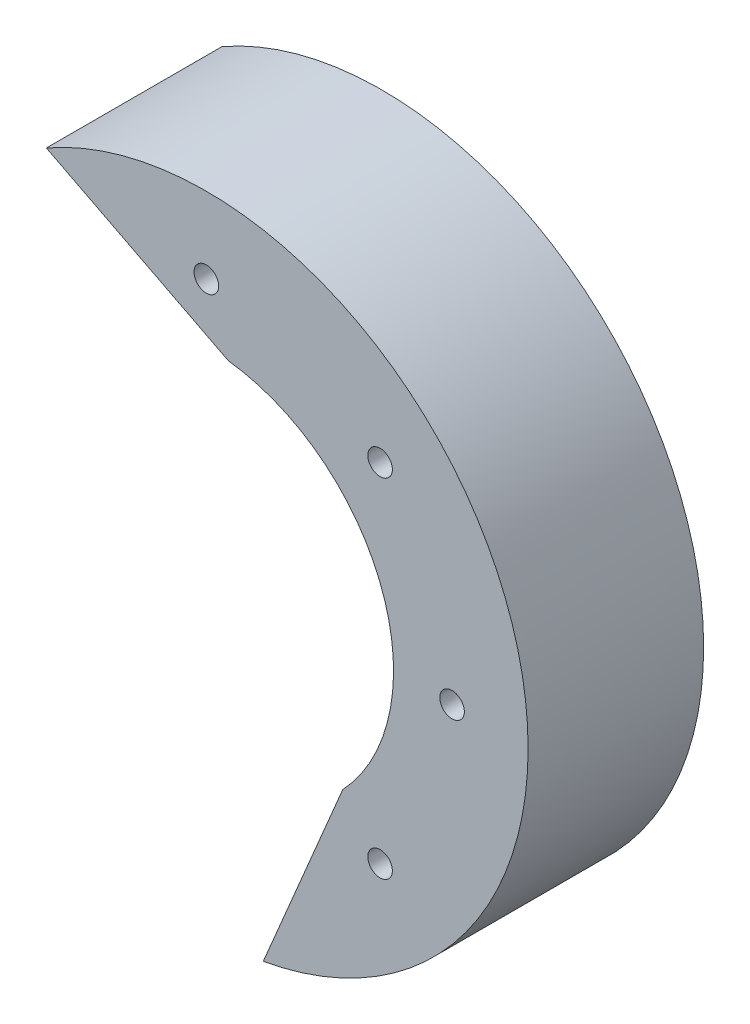
SolidWorks part; units mm, degrees
material "尼龙 101"
ref_plane "前视基准面" through (0, 0, 0) normal (0, 0, 1) x (1, 0, 0)
ref_plane "上视基准面" through (0, 0, 0) normal (0, 1, 0) x (1, 0, 0)
ref_plane "右视基准面" through (0, 0, 0) normal (1, 0, 0) x (0, 0, -1)
sketch "草图1" plane through (0, 0, 0) normal (0, 0, 1) x (1, 0, 0)
  line L0 (0, 55) -> (0, -55) construction
  line L1 (-55, 0) -> (55, 0) construction
  line L2 (0, 0) -> (-138.5641, 80) construction
  line L3 (0, 0) -> (-54.7232, -150.3508) construction
  line L4 (-27.3421, 47.7222) -> (3.7722, 31.7769)
  line L7 (9.73, -54.1325) -> (23.3155, -21.9178)
  arc A0 (9.73, -54.1325) -> (-27.3421, 47.7222) centre (0, 0) ccw
  arc A1 (23.3155, -21.9178) -> (3.7722, 31.7769) centre (0, 0) ccw
  circle A3 centre (-138.5641, 80) radius 22 construction
  circle A4 centre (0, 0) radius 30 construction
  circle A6 centre (-54.7232, -150.3508) radius 22 construction
  dimension "D1" = 110
  dimension "D2" = 64
  dimension "D4" = 160
  dimension "D5" = 44
  dimension "D6" = 60
  dimension "D8" = 20
  dimension "D9" = 44
  dimension "D3" = 150
  dimension "D7" = 160
extrude "凸台-拉伸1" add sketch "草图1" along normal blind 30
sketch "草图2" plane through (0, 0, 30) normal (0, 0, 1) x (1, 0, 0)
  circle A0 centre (0, 0) radius 42 construction
  point P3 (0, 42)
  point P6 (29.6985, 29.6985)
  point P7 (42, 0)
  point P8 (29.6985, -29.6985)
  point P9 (0, -42)
  point P10 (-29.6985, -29.6985)
  point P11 (-42, 0)
  point P12 (-29.6985, 29.6985)
  dimension "D1" = 84
  dimension "D2" = 8
hole_wizard "Ø4.2 (4.2) 直径孔1" positions "3D草图2" profile "草图6" hole size "Ø4.2" standard "GB" end condition through all
sketch3d "3D草图2"
  point P0 (0, 42, 30)
  point P3 (29.6985, 29.6985, 30)
  point P6 (42, 0, 30)
  point P9 (29.6985, -29.6985, 30)
sketch "草图6" plane through (0, 42, 30) normal (1, 0, 0) x (0, -1, 0)
  line L0 (0, 0) -> (0, 30)
  line L1 (0, 30) -> (2.1, 30)
  line L2 (2.1, 30) -> (2.1, 0)
  line L5 (2.1, 0) -> (0, 0)
  line L11 (0, -6.35) -> (0, 107.95) construction
  dimension "通孔孔直径" = 4.2
  dimension "通孔孔深度" = 30
sketch "草图7" plane through (0, 0, 0) normal (0, 0, -1) x (-1, 0, 0)
  circle A0 centre (0, 42) radius 5
  circle A1 centre (-29.6985, 29.6985) radius 5
  circle A2 centre (-42, 0) radius 5
  circle A3 centre (-29.6985, -29.6985) radius 5
  dimension "D1" = 10
  dimension "D2" = 10
  dimension "D3" = 10
  dimension "D4" = 10
extrude "切除-拉伸1" cut sketch "草图7" against normal blind 20
